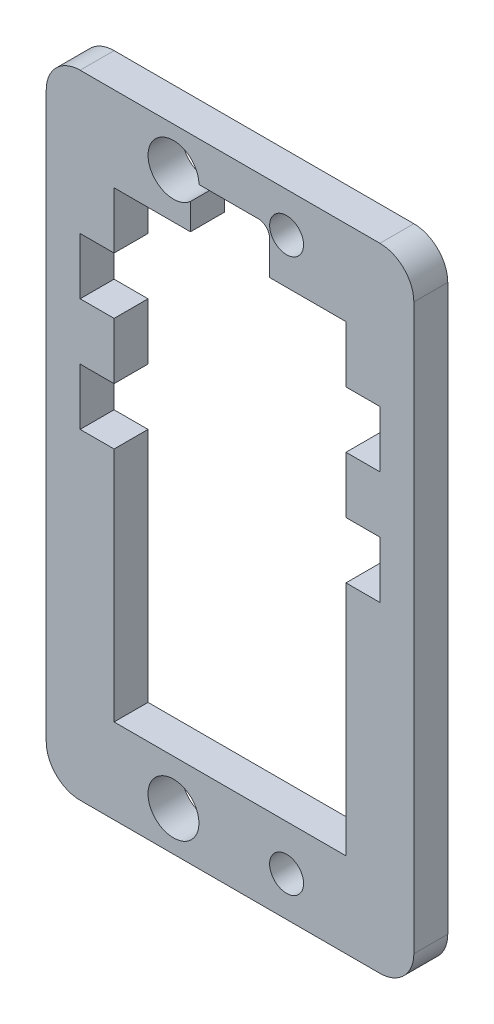
SolidWorks part; units mm, degrees
ref_plane "Alzado" through (0, 0, 0) normal (0, 0, 1) x (1, 0, 0)
ref_plane "Planta" through (0, 0, 0) normal (0, 1, 0) x (1, 0, 0)
ref_plane "Vista lateral" through (0, 0, 0) normal (1, 0, 0) x (0, 0, -1)
sketch "Sketch1" plane through (0, 0, 0) normal (0, 0, 1) x (1, 0, 0)
  line L0 (-13.25, 27.95) -> (13.25, 27.95)
  line L1 (-10.25, 20.45) -> (-3.5, 20.45)
  line L2 (-10.25, 20.45) -> (-10.25, 15.45)
  line L3 (-10.25, -20.45) -> (10.25, -20.45)
  line L4 (10.25, 20.45) -> (10.25, 15.45)
  line L5 (-10.25, 20.45) -> (10.25, -20.45) construction
  line L6 (-10.25, -20.45) -> (10.25, 20.45) construction
  line L7 (16.25, 24.95) -> (16.25, -24.95)
  line L8 (13.25, -27.95) -> (-13.25, -27.95)
  line L9 (-16.25, -24.95) -> (-16.25, 24.95)
  line L10 (0, 27.95) -> (0, -27.95) construction
  line L11 (16.25, 0) -> (-16.25, 0) construction
  line L12 (-10.25, 15.45) -> (-13.25, 15.45)
  line L13 (-13.25, 15.45) -> (-13.25, 10.45)
  line L14 (-13.25, 10.45) -> (-10.25, 10.45)
  line L15 (-10.25, 5.45) -> (-13.25, 5.45)
  line L16 (-13.25, 5.45) -> (-13.25, 0.45)
  line L17 (-13.25, 0.45) -> (-10.25, 0.45)
  line L18 (10.25, 15.45) -> (13.25, 15.45)
  line L19 (13.25, 15.45) -> (13.25, 10.45)
  line L20 (13.25, 10.45) -> (10.25, 10.45)
  line L21 (10.25, 5.45) -> (13.25, 5.45)
  line L22 (13.25, 5.45) -> (13.25, 0.45)
  line L23 (13.25, 0.45) -> (10.25, 0.45)
  line L24 (-10.25, 10.45) -> (-10.25, 5.45)
  line L25 (-10.25, 0.45) -> (-10.25, -20.45)
  line L26 (10.25, 0.45) -> (10.25, -20.45)
  line L27 (10.25, 10.45) -> (10.25, 5.45)
  line L28 (-5, 24.45) -> (5, 24.45) construction
  line L29 (-3.5, 20.45) -> (-3.5, 22.7729)
  line L30 (-2.75, 24.45) -> (2.5, 24.45)
  line L31 (3.5, 23.45) -> (3.5, 20.45)
  line L32 (-3.5, 24.45) -> (-2.75, 24.45) construction
  line L33 (-3.5, 22.7729) -> (-3.5, 24.45) construction
  line L34 (3.5, 20.45) -> (10.25, 20.45)
  arc A0 (13.25, 27.95) -> (16.25, 24.95) centre (13.25, 24.95) cw
  arc A1 (16.25, -24.95) -> (13.25, -27.95) centre (13.25, -24.95) cw
  arc A2 (-13.25, -27.95) -> (-16.25, -24.95) centre (-13.25, -24.95) cw
  arc A3 (-16.25, 24.95) -> (-13.25, 27.95) centre (-13.25, 24.95) cw
  arc A4 (-2.75, 24.45) -> (-3.5, 22.7729) centre (-5, 24.45) ccw
  circle A5 centre (5, 24.45) radius 1.5
  circle A6 centre (5, -24.45) radius 1.5
  circle A7 centre (-5, -24.45) radius 2.25
  arc A8 (2.5, 24.45) -> (3.5, 23.45) centre (2.5, 23.45) cw
  point P0 (0, 0)
  point P22 (0, 0)
  dimension "D4" = 3
  dimension "D14" = 4.5
  dimension "D15" = 3
  dimension "D16" = 1
  dimension "D1" = 20.5
  dimension "D2" = 40.9
  dimension "D3" = 7.5
  dimension "D5" = 6
  dimension "D6" = 3
  dimension "D7" = 3
  dimension "D8" = 5
  dimension "D9" = 5
  dimension "D10" = 5
  dimension "D11" = 5
  dimension "D13" = 10
  dimension "D17" = 7
  dimension "D18" = 4
extrude "Boss-Extrude1" add sketch "Sketch1" along normal blind 3
